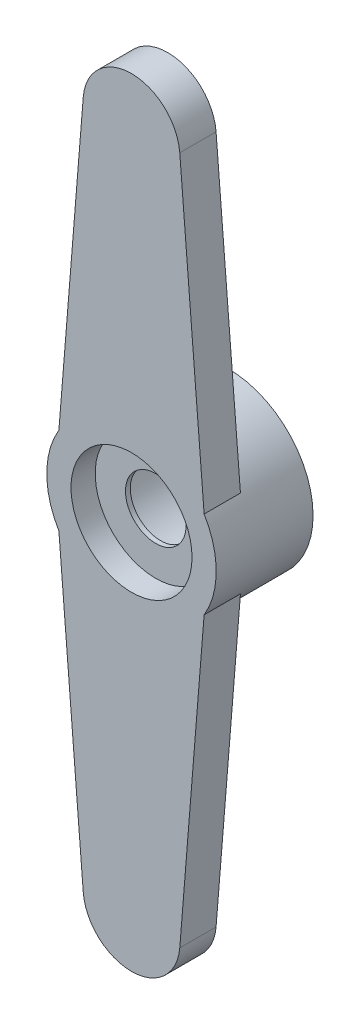
SolidWorks part; units mm, degrees
material "ABS"
ref_plane "Front" through (0, 0, 0) normal (0, 0, 1) x (1, 0, 0)
ref_plane "Top" through (0, 0, 0) normal (0, 1, 0) x (1, 0, 0)
ref_plane "Right" through (0, 0, 0) normal (1, 0, 0) x (0, 0, -1)
sketch "Sketch1" plane through (0, 0, 0) normal (0, 0, 1) x (1, 0, 0)
  circle A0 centre (0, 0) radius 3.5
  circle A1 centre (0, 0) radius 2.5
  dimension "D1" = 7
  dimension "D2" = 5
extrude "Boss-Extrude1" add sketch "Sketch1" along normal blind 2.8
sketch "Sketch2" plane through (0, 0, 2.8) normal (0, 0, 1) x (1, 0, 0)
  circle A0 centre (0, 0) radius 3.5
  circle A1 centre (0, 0) radius 1.25
  dimension "D1" = 2.5
extrude "Boss-Extrude2" add sketch "Sketch2" along normal blind 0.2
sketch "Sketch3" plane through (0, 0, 3) normal (0, 0, 1) x (1, 0, 0)
  circle A0 centre (0, 0) radius 3.5
  circle A1 centre (0, 0) radius 2.5
  dimension "D1" = 5
extrude "Boss-Extrude3" add sketch "Sketch3" along normal blind 1
sketch "Sketch4" plane through (0, 0, 4) normal (0, 0, 1) x (1, 0, 0)
  line L0 (-3, -1.8028) -> (-1.9935, -14.2233)
  line L1 (3, -1.8028) -> (1.9935, -14.2233)
  circle A0 centre (0, 0) radius 3.5 construction
  arc A1 (-1.9935, -14.2233) -> (1.9935, -14.2233) centre (0, -14.0618) ccw
  arc A2 (-3, -1.8028) -> (3, -1.8028) centre (0, 0) ccw
  dimension "D2" = 16.0618
  dimension "D3" = 2
  dimension "D1" = 6
extrude "Boss-Extrude4" add sketch "Sketch4" against normal blind 1.5
mirror "Mirror1" about plane through (0, 0, 0) normal (0, 1, 0) of "Boss-Extrude4"
